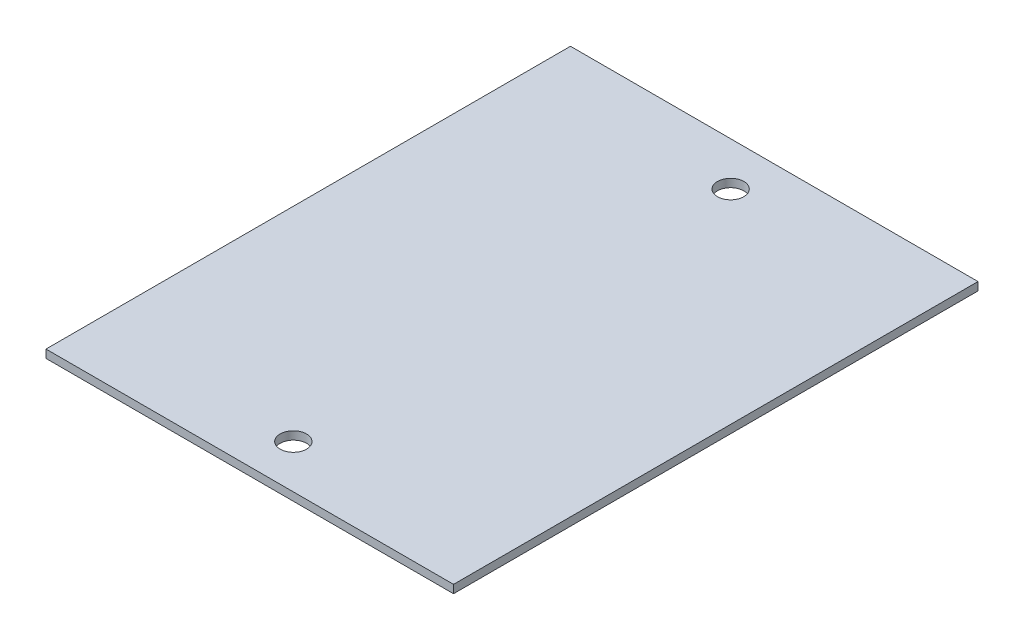
SolidWorks part; units mm, degrees
ref_plane "Front Plane" through (0, 0, 0) normal (0, 0, 1) x (1, 0, 0)
ref_plane "Top Plane" through (0, 0, 0) normal (0, 1, 0) x (1, 0, 0)
ref_plane "Right Plane" through (0, 0, 0) normal (1, 0, 0) x (0, 0, -1)
sketch "Sketch1" plane through (0, 0, 0) normal (0, 1, 0) x (1, 0, 0)
  line L0 (0, 0) -> (0, 34.0678) construction
  line L2 (-31.75, 40.8592) -> (31.75, 40.8592)
  line L3 (-31.75, 40.8592) -> (-31.75, -40.8592)
  line L4 (-31.75, -40.8592) -> (31.75, -40.8592)
  line L5 (0, 0) -> (0, -34.0678) construction
  line L6 (31.75, 40.8592) -> (31.75, -40.8592)
  line L7 (-31.75, 40.8592) -> (31.75, -40.8592) construction
  line L8 (-31.75, -40.8592) -> (31.75, 40.8592) construction
  circle A0 centre (0, 34.0678) radius 2.0574
  circle A1 centre (0, -34.0678) radius 2.0574
  point P0 (0, 0)
  dimension "D2" = 4.1148
  dimension "D1" = 34.0678
extrude "Boss-Extrude1" add sketch "Sketch1" along normal blind 1.27
